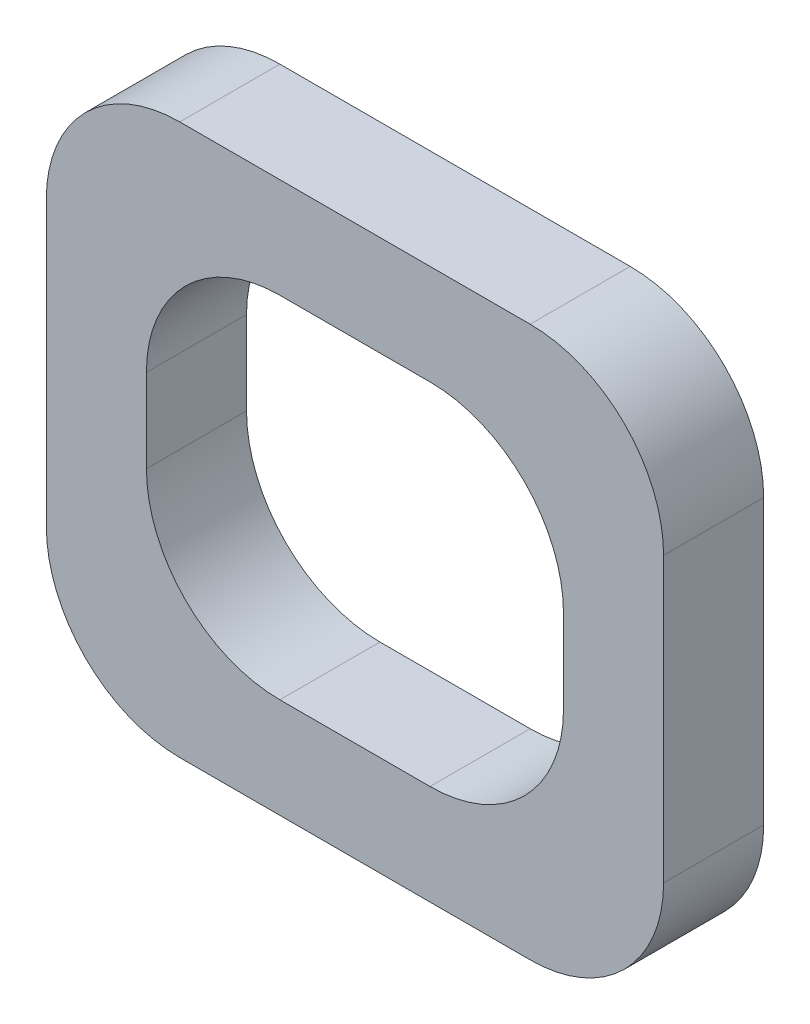
SolidWorks part; units mm, degrees
ref_plane "Front Plane" through (0, 0, 0) normal (0, 0, 1) x (1, 0, 0)
ref_plane "Top Plane" through (0, 0, 0) normal (0, 1, 0) x (1, 0, 0)
ref_plane "Right Plane" through (0, 0, 0) normal (1, 0, 0) x (0, 0, -1)
sketch "Sketch1" plane through (0, 0, 0) normal (0, 0, 1) x (1, 0, 0)
  line L1 (-6.25, 5.25) -> (6.25, 5.25)
  line L2 (-6.25, 5.25) -> (-6.25, -5.25)
  line L3 (-6.25, -5.25) -> (6.25, -5.25)
  line L4 (6.25, 5.25) -> (6.25, -5.25)
  line L5 (-6.25, 5.25) -> (6.25, -5.25) construction
  line L6 (-6.25, -5.25) -> (6.25, 5.25) construction
  line L7 (-9.25, 8.25) -> (9.25, 8.25)
  line L8 (-9.25, 8.25) -> (-9.25, -8.25)
  line L9 (-9.25, -8.25) -> (9.25, -8.25)
  line L10 (9.25, 8.25) -> (9.25, -8.25)
  line L11 (-9.25, 8.25) -> (9.25, -8.25) construction
  line L12 (-9.25, -8.25) -> (9.25, 8.25) construction
  point P0 (0, 0)
  point P5 (0, 0)
  dimension "D1" = 10.5
  dimension "D2" = 12.5
  dimension "D3" = 16.5
  dimension "D4" = 18.5
extrude "Boss-Extrude1" add sketch "Sketch1" along normal blind 3
fillet "Fillet1" radius 4 8 edges at (-9.25, 8.25, 1.5) (-6.25, -5.25, 1.5) (-6.25, 5.25, 1.5) (6.25, -5.25, 1.5) (9.25, -8.25, 1.5) (-9.25, -8.25, 1.5) (6.25, 5.25, 1.5) (9.25, 8.25, 1.5)
